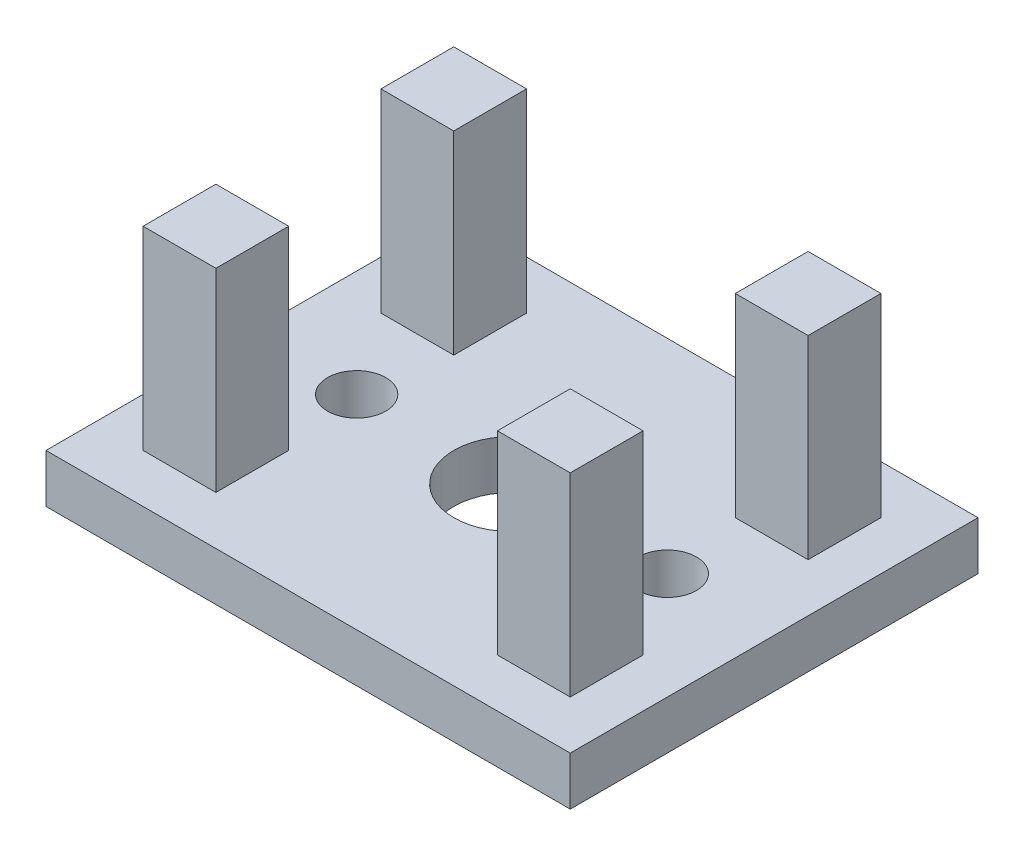
SolidWorks part; units mm, degrees
ref_plane "Front Plane" through (0, 0, 0) normal (0, 0, 1) x (1, 0, 0)
ref_plane "Top Plane" through (0, 0, 0) normal (0, 1, 0) x (1, 0, 0)
ref_plane "Right Plane" through (0, 0, 0) normal (1, 0, 0) x (0, 0, -1)
sketch "Sketch4" plane through (0, 0, 0) normal (0, 1, 0) x (1, 0, 0)
  line L1 (-27, 21) -> (27, 21)
  line L2 (-27, 21) -> (-27, -21)
  line L3 (-27, -21) -> (27, -21)
  line L4 (27, 21) -> (27, -21)
  dimension "D1" = 27
  dimension "D2" = 54
  dimension "D3" = 21
  dimension "D4" = 42
extrude "Boss-Extrude1" add sketch "Sketch4" along normal blind 5
sketch "Sketch5" plane through (0, 5, 0) normal (0, 1, 0) x (1, 0, 0)
  circle A0 centre (0, 0) radius 6
  circle A1 centre (-16, 0) radius 3
  circle A2 centre (16, 0) radius 3
  dimension "D1" = 32
  dimension "D2" = 16
extrude "Cut-Extrude1" cut sketch "Sketch5" against normal blind 5
sketch "Sketch6" plane through (0, 5, 0) normal (0, 1, 0) x (1, 0, 0)
  line L1 (-22, 16) -> (-14.5, 16)
  line L2 (-22, 16) -> (-22, 8.5)
  line L3 (-22, 8.5) -> (-14.5, 8.5)
  line L4 (-14.5, 16) -> (-14.5, 8.5)
  line L28 (-27, 21) -> (-27, -21) construction
  line L29 (27, 21) -> (-27, 21) construction
  line L30 (-27, -21) -> (27, -21) construction
  line L31 (27, -21) -> (27, 21) construction
  line L32 (0, 21) -> (0, -21)
  line L33 (-27, 0) -> (27, 0)
  line L34 (22, 8.5) -> (14.5, 8.5)
  line L35 (14.5, 16) -> (14.5, 8.5)
  line L36 (22, 16) -> (14.5, 16)
  line L37 (22, 16) -> (22, 8.5)
  line L38 (22, -16) -> (22, -8.5)
  line L39 (22, -16) -> (14.5, -16)
  line L40 (14.5, -16) -> (14.5, -8.5)
  line L41 (22, -8.5) -> (14.5, -8.5)
  line L42 (-22, -8.5) -> (-14.5, -8.5)
  line L43 (-14.5, -16) -> (-14.5, -8.5)
  line L44 (-22, -16) -> (-14.5, -16)
  line L45 (-22, -16) -> (-22, -8.5)
  dimension "D1" = 7.5
  dimension "D2" = 7.5
  dimension "D3" = 5
  dimension "D4" = 5
extrude "Boss-Extrude3" add sketch "Sketch6" along normal blind 20 contours L4 L1 L2 L3 | L37 L36 L35 L34 | L45 L44 L43 L42 | L38 L41 L40 L39
